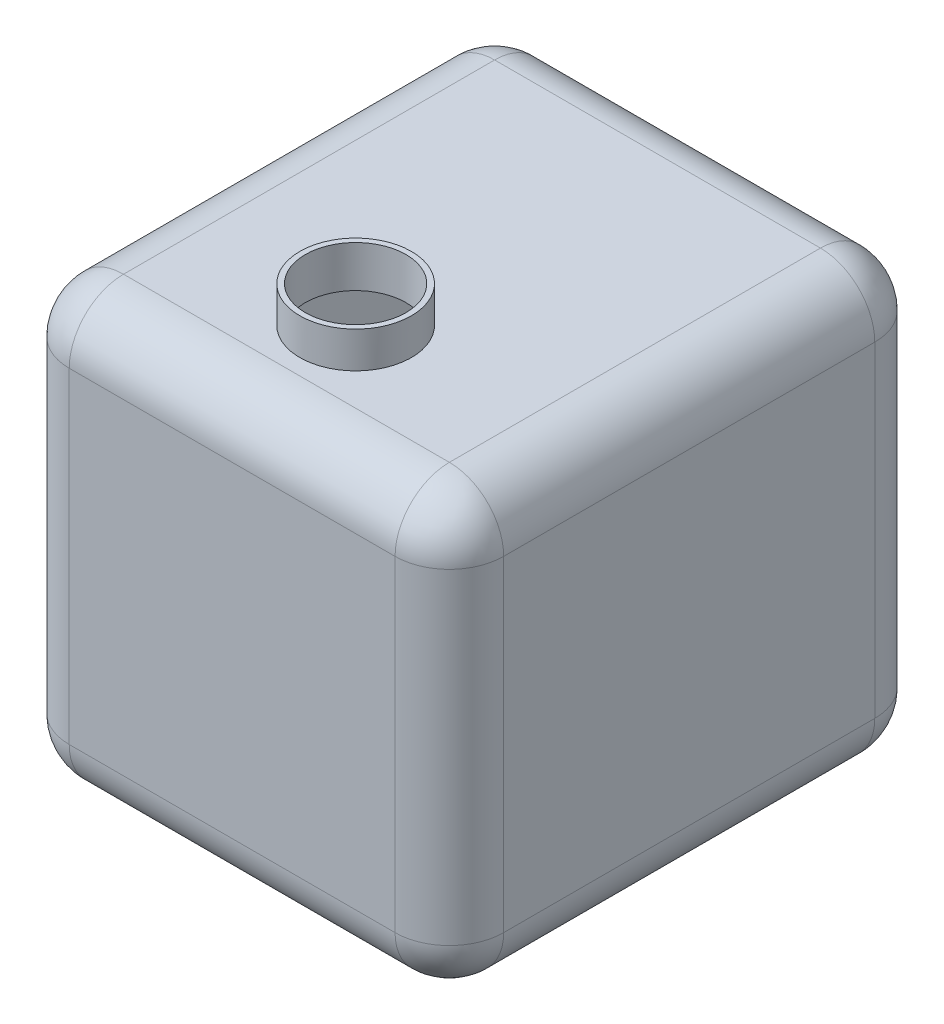
SolidWorks part; units mm, degrees
ref_plane "Alzado" through (0, 0, 0) normal (0, 0, 1) x (1, 0, 0)
ref_plane "Planta" through (0, 0, 0) normal (0, 1, 0) x (1, 0, 0)
ref_plane "Vista lateral" through (0, 0, 0) normal (1, 0, 0) x (0, 0, -1)
sketch "Croquis1" plane through (0, 0, 0) normal (0, -1, 0) x (1, 0, 0)
  line L1 (-48.3767, 245.8296) -> (191.6233, 245.8296)
  line L2 (-48.3767, 245.8296) -> (-48.3767, -19.1704)
  line L3 (-48.3767, -19.1704) -> (191.6233, -19.1704)
  line L4 (191.6233, 245.8296) -> (191.6233, -19.1704)
  dimension "D1" = 240
  dimension "D2" = 265
extrude "Saliente-Extruir1" add sketch "Croquis1" against normal blind 240
fillet "Redondeo1" radius 30 4 edges at (191.6233, 120, -19.1704) (191.6233, 120, 245.8296) (-48.3767, 120, -19.1704) (-48.3767, 120, 245.8296)
fillet "Redondeo2" radius 30 16 edges at (71.6233, 0, 245.8296) (-39.5899, 0, 237.0428) (-48.3767, 0, 113.3296) (-39.5899, 0, -10.3836) (71.6233, 0, -19.1704) (182.8366, 0, -10.3836) (191.6233, 0, 113.3296) (182.8366, 0, 237.0428) (-39.5899, 240, 237.0428) (71.6233, 240, 245.8296) (182.8366, 240, 237.0428) (191.6233, 240, 113.3296) (182.8366, 240, -10.3836) (71.6233, 240, -19.1704) (-39.5899, 240, -10.3836) (-48.3767, 240, 113.3296)
sketch "Croquis2" plane through (0, 240, 0) normal (0, 1, 0) x (1, 0, 0)
  circle A0 centre (70.2222, -176.2117) radius 30.8115
extrude "Saliente-Extruir2" add sketch "Croquis2" along normal blind 20
shell "Vaciado1" thickness 3
